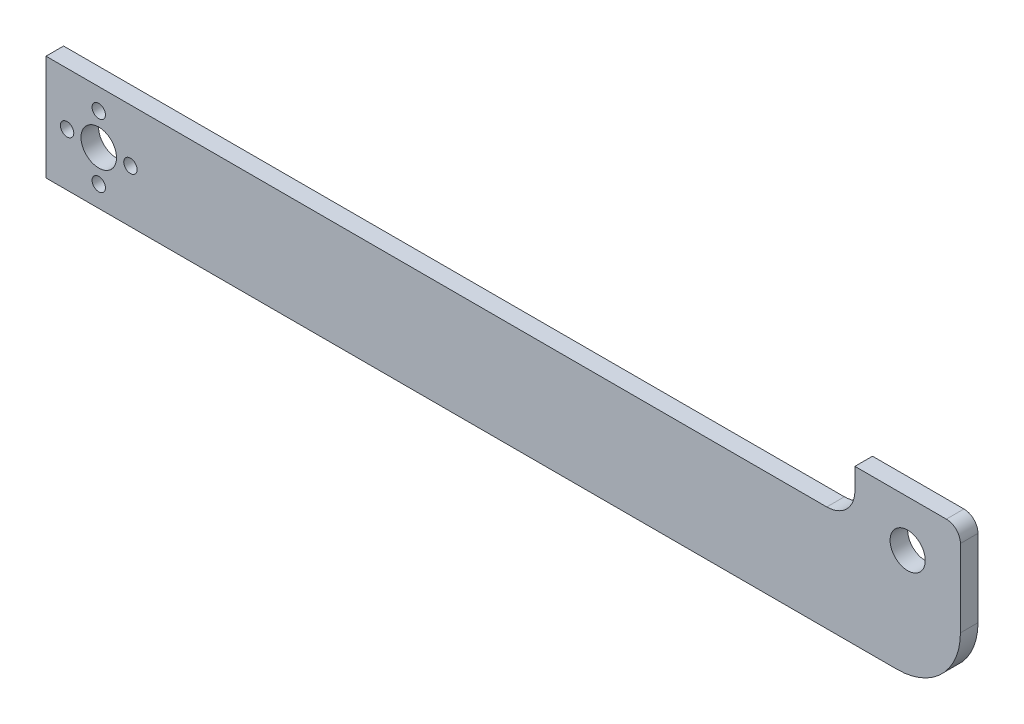
SolidWorks part; units mm, degrees
ref_plane "Front" through (0, 0, 0) normal (0, 0, 1) x (1, 0, 0)
ref_plane "Top" through (0, 0, 0) normal (0, 1, 0) x (1, 0, 0)
ref_plane "Right" through (0, 0, 0) normal (1, 0, 0) x (0, 0, -1)
sketch "Sketch1" plane through (0, 0, 0) normal (0, 0, 1) x (1, 0, 0)
  line L0 (273.05, 36.83) -> (273.05, 29.21)
  line L1 (-19.05, 19.05) -> (262.89, 19.05)
  line L2 (-19.05, 19.05) -> (-19.05, -19.05)
  line L3 (-19.05, -19.05) -> (285.1901, -19.05)
  line L5 (285.1901, -19.05) -> (288.29, -19.05)
  line L7 (273.05, 36.83) -> (311.15, 36.83)
  line L8 (311.15, 3.81) -> (311.15, 36.83)
  circle A0 centre (0, 0) radius 6.4135
  circle A1 centre (0, 11.43) radius 2.413
  circle A2 centre (0, 0) radius 11.43 construction
  circle A3 centre (11.43, 0) radius 2.413
  circle A4 centre (0, -11.43) radius 2.413
  circle A5 centre (-11.43, 0) radius 2.413
  arc A7 (288.29, -19.05) -> (311.15, 3.81) centre (288.29, 3.81) ccw
  circle A8 centre (292.1, 20.066) radius 6.35
  circle A13 centre (292.1, 20.066) radius 19.05 construction
  arc A15 (273.05, 29.21) -> (262.89, 19.05) centre (262.89, 29.21) cw
  point P15 (0, 0)
  point P17 (-19.05, 0)
  point P23 (322.7312, -12.5483)
  point P38 (292.1, 36.83)
  dimension "D1" = 12.827
  dimension "D2" = 4.826
  dimension "D3" = 22.86
  dimension "D5" = 19.05
  dimension "D8" = 10.16
  dimension "D9" = 22.86
  dimension "D12" = 12.7
  dimension "D13" = 16.764
  dimension "D14" = 38.1
  dimension "D15" = 38.1
  dimension "D6" = 38.1
  dimension "D7" = 330.2
  dimension "D10" = 38.1
  dimension "D11" = 33.02
  dimension "D4" = 4
extrude "Boss-Extrude1" add sketch "Sketch1" along normal blind 6.35
fillet "Fillet1" radius 5.08 1 edges at (311.15, 36.83, 3.175)
